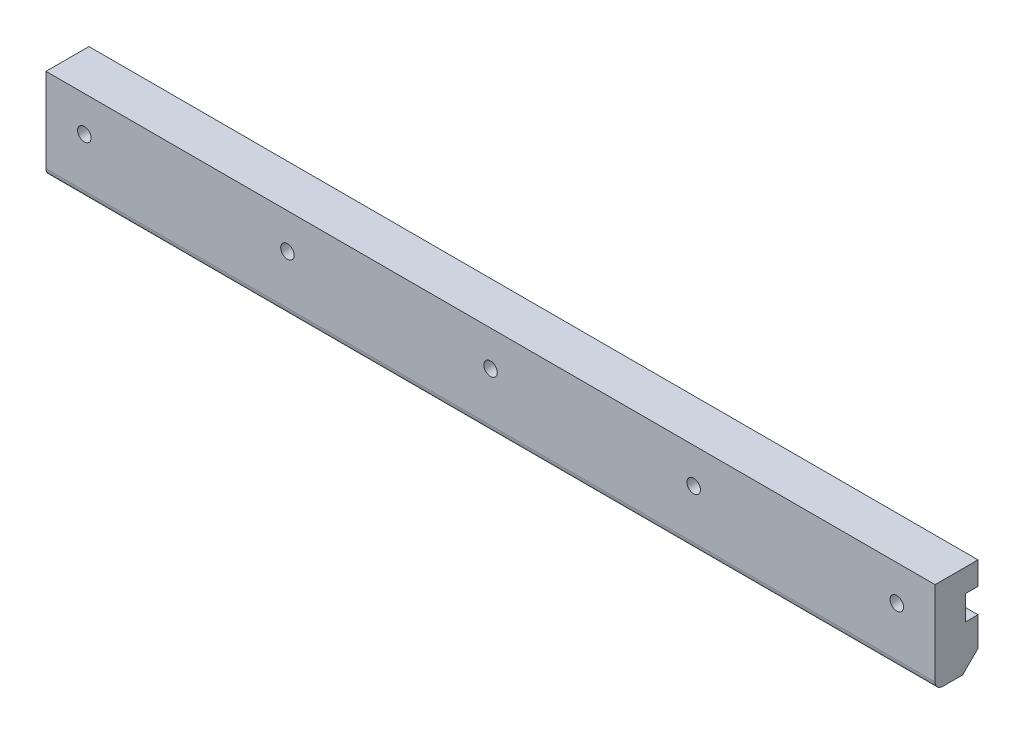
SolidWorks part; units mm, degrees
ref_plane "前基準面" through (0, 0, 0) normal (0, 0, 1) x (1, 0, 0)
ref_plane "上基準面" through (0, 0, 0) normal (0, 1, 0) x (1, 0, 0)
ref_plane "右基準面" through (0, 0, 0) normal (1, 0, 0) x (0, 0, -1)
sketch "草圖1" plane through (0, 0, 0) normal (1, 0, 0) x (0, 0, -1)
  line L1 (0, 0) -> (28, 0)
  line L2 (0, 0) -> (0, 29)
  line L3 (0, 29) -> (28, 29)
  line L4 (28, 0) -> (28, 29)
  line L5 (0, 29) -> (20, 29)
  line L6 (0, 29) -> (0, 45)
  line L7 (0, 45) -> (20, 45)
  line L8 (20, 29) -> (20, 45)
  line L9 (0, 45) -> (28, 45)
  line L10 (0, 45) -> (0, 60)
  line L11 (0, 60) -> (28, 60)
  line L12 (28, 45) -> (28, 60)
  dimension "D1" = 15
  dimension "D2" = 16
  dimension "D3" = 60
  dimension "D4" = 28
  dimension "D5" = 28
  dimension "D6" = 8
extrude "填料-伸長1" add sketch "草圖1" along normal blind 580 contours L9 L12 L11 L10 L7 | L3 L8 L7 L6 | L1 L4 L3 L2
chamfer "導角1" distance 10 angle 45 1 edges at (290, 0, -28)
hole_wizard "M10x1.25 螺紋孔1" positions "草圖2" profile "草圖3" tap size "M10x1.25" standard "ISO"
sketch "草圖2" plane through (0, 0, -20) normal (0, 0, -1) x (-1, 0, 0)
  line L0 (-422.5, 37) -> (-555, 37)
  line L2 (-422.5, 37) -> (-290, 37)
  line L4 (-290, 37) -> (-157.5, 37)
  line L5 (-157.5, 37) -> (-25, 37)
  line L7 (-580, 29) -> (-580, 45) construction
  line L8 (-580, 60) -> (0, 60) construction
  point P0 (-555, 37)
  point P2 (-422.5, 37)
  point P4 (-290, 37)
  point P6 (-157.5, 37)
  point P8 (-25, 37)
  dimension "D1" = 25
  dimension "D2" = 132.5
  dimension "D3" = 132.5
  dimension "D4" = 132.5
  dimension "D5" = 132.5
  dimension "D6" = 23
sketch "草圖3" plane through (555, 37, -20) normal (1, 0, 0) x (0, 1, 0)
  line L0 (0, 0) -> (0, 61.6438)
  line L1 (0, 61.6438) -> (4.4, 59)
  line L2 (4.4, 59) -> (4.4, 0)
  line L5 (4.4, 0) -> (0, 0)
  line L10 (0, 61.6438) -> (-4.4, 59) construction
  line L11 (0, -6.35) -> (0, 107.95) construction
  dimension "螺孔鑽直徑" = 8.8
  dimension "螺孔鑽深度" = 59
  dimension "導頭角度" = 118
cosmetic thread "鑽孔螺紋1" parameters "D1"=20, "D2"=10
cosmetic thread "鑽孔螺紋2" parameters "D1"=20, "D2"=10
cosmetic thread "鑽孔螺紋3" parameters "D1"=20, "D2"=10
cosmetic thread "鑽孔螺紋4" parameters "D1"=20, "D2"=10
cosmetic thread "鑽孔螺紋5" parameters "D1"=20, "D2"=10
fillet "圓角1" radius 5 1 edges at (290, 0, 0)
